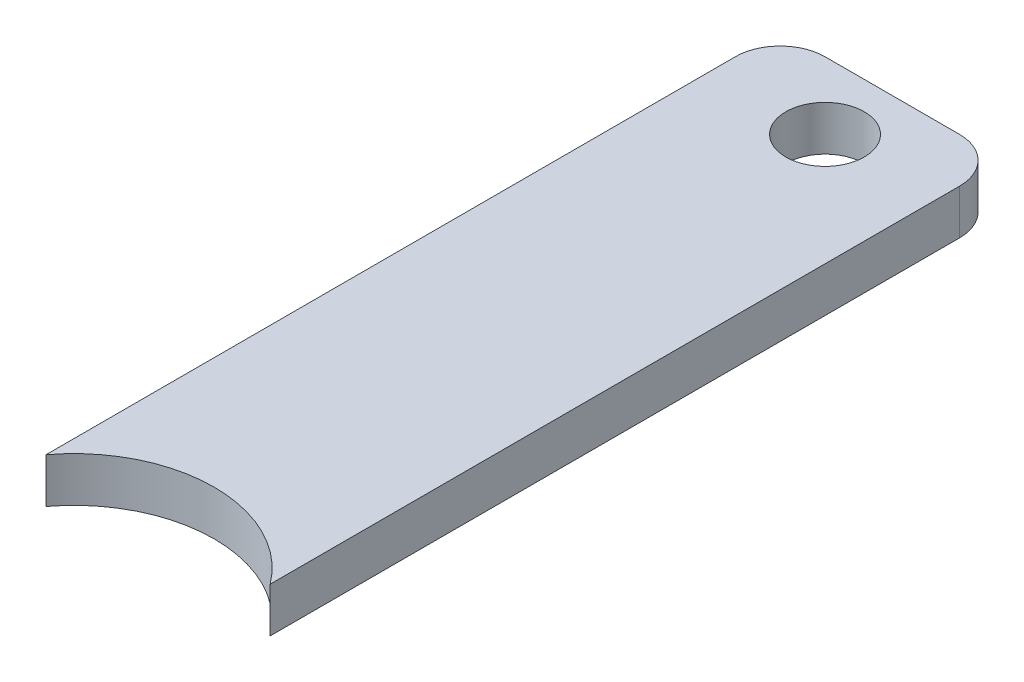
SolidWorks part; units mm, degrees
material "ASTM A36 Steel"
ref_plane "Front Plane" through (0, 0, 0) normal (0, 0, 1) x (1, 0, 0)
ref_plane "Top Plane" through (0, 0, 0) normal (0, 1, 0) x (1, 0, 0)
ref_plane "Right Plane" through (0, 0, 0) normal (1, 0, 0) x (0, 0, -1)
sketch "Sketch1" plane through (0, 0, 0) normal (0, 1, 0) x (1, 0, 0)
  line L1 (-10, 14.5) -> (-10, 76)
  line L2 (10, 14.5) -> (10, 76)
  line L3 (6, 80) -> (-6, 80)
  circle A1 centre (0, 74) radius 3.5
  arc A2 (10, 76) -> (6, 80) centre (6, 76) ccw
  arc A3 (-10, 76) -> (-6, 80) centre (-6, 76) cw
  arc A4 (10, 14.5) -> (-10, 14.5) centre (0, 7) ccw
  dimension "D2" = 7
  dimension "D3" = 6
  dimension "D4" = 4
  dimension "D5" = 25
extrude "Boss-Extrude1" add sketch "Sketch1" along normal blind 4
